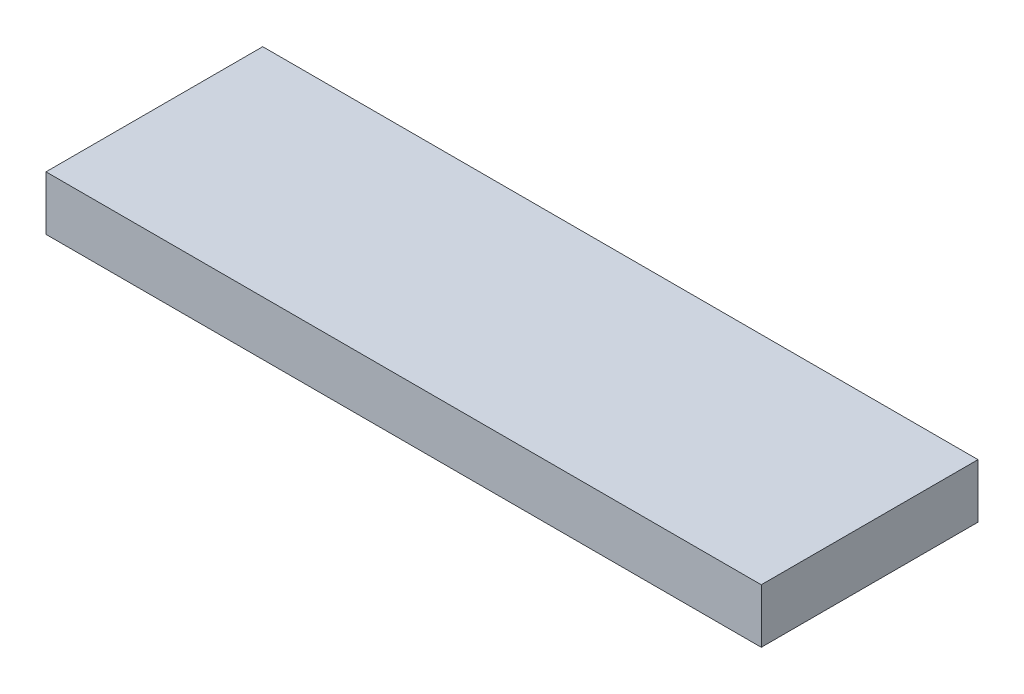
SolidWorks part; units mm, degrees
ref_plane "Front Plane" through (0, 0, 0) normal (0, 0, 1) x (1, 0, 0)
ref_plane "Top Plane" through (0, 0, 0) normal (0, 1, 0) x (1, 0, 0)
ref_plane "Right Plane" through (0, 0, 0) normal (1, 0, 0) x (0, 0, -1)
sketch "Sketch1" plane through (0, 0, 0) normal (0, 1, 0) x (1, 0, 0)
  line L1 (41.91, -12.7) -> (-41.91, -12.7)
  line L2 (41.91, -12.7) -> (41.91, 12.7)
  line L3 (41.91, 12.7) -> (-41.91, 12.7)
  line L4 (-41.91, -12.7) -> (-41.91, 12.7)
  line L5 (41.91, -12.7) -> (-41.91, 12.7) construction
  line L6 (41.91, 12.7) -> (-41.91, -12.7) construction
  point P0 (0, 0)
  dimension "D1" = 83.82
  dimension "D2" = 25.4
extrude "Box" add sketch "Sketch1" along normal blind 6.35
sketch "Sketch5" plane through (0, 0, 0) normal (0, 1, 0) x (1, 0, 0)
  line L0 (-13.3549, 0) -> (-20.9351, 0) construction
  line L1 (-13.3549, -5.08) -> (-20.9351, -5.08)
  line L2 (-13.3549, 5.08) -> (-20.9351, 5.08)
  line L3 (0, 0) -> (0, 12.7) construction
  line L4 (41.91, 12.7) -> (-41.91, 12.7) construction
  line L5 (0, -12.7) -> (0, -12.6999) construction
  line L7 (-41.91, -12.7) -> (41.91, -12.7) construction
  line L8 (0, 0) -> (0, -12.6882) construction
  line L9 (13.3549, 0) -> (20.9351, 0) construction
  line L10 (13.3549, -5.08) -> (20.9351, -5.08)
  line L11 (13.3549, 5.08) -> (20.9351, 5.08)
  arc A0 (-13.3549, -5.08) -> (-13.3549, 5.08) centre (-13.3549, 0) ccw
  arc A1 (-20.9351, 5.08) -> (-20.9351, -5.08) centre (-20.9351, 0) ccw
  arc A2 (13.3549, -5.08) -> (13.3549, 5.08) centre (13.3549, 0) cw
  arc A3 (20.9351, 5.08) -> (20.9351, -5.08) centre (20.9351, 0) cw
  point P3 (-17.145, 0)
  point P19 (17.145, 0)
extrude "Cut-Extrude1" cut sketch "Sketch5" along normal blind 3.175
